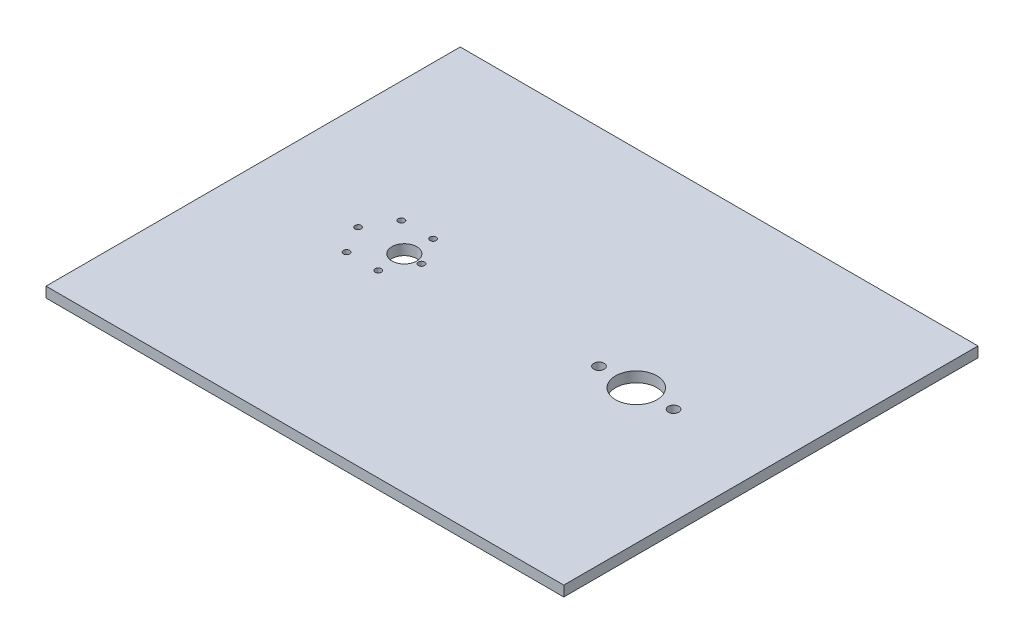
SolidWorks part; units mm, degrees
ref_plane "Front Plane" through (0, 0, 0) normal (0, 0, 1) x (1, 0, 0)
ref_plane "Top Plane" through (0, 0, 0) normal (0, 1, 0) x (1, 0, 0)
ref_plane "Right Plane" through (0, 0, 0) normal (1, 0, 0) x (0, 0, -1)
sketch "Sketch1" plane through (0, 0, 0) normal (0, 1, 0) x (1, 0, 0)
  line L0 (-125, 0) -> (125, 0) construction
  line L1 (-125, 100) -> (125, 100)
  line L2 (-125, 100) -> (-125, -100)
  line L3 (-125, -100) -> (125, -100)
  line L4 (125, 100) -> (125, -100)
  line L5 (-125, 100) -> (125, -100) construction
  line L6 (-125, -100) -> (125, 100) construction
  circle A0 centre (60, 0) radius 10
  circle A1 centre (78, 0) radius 2.5
  circle A2 centre (42, 0) radius 2.5
  circle A4 centre (-43.7, 0) radius 1.5
  circle A5 centre (-51.35, -13.2502) radius 1.5
  circle A6 centre (-66.65, -13.2502) radius 1.5
  circle A7 centre (-74.3, 0) radius 1.5
  circle A8 centre (-66.65, 13.2502) radius 1.5
  circle A9 centre (-51.35, 13.2502) radius 1.5
  circle A10 centre (-52, 0) radius 6
  point P0 (0, 0)
  point P31 (-59, 0)
  dimension "D3" = 20
  dimension "D4" = 5
  dimension "D5" = 5
  dimension "D9" = 112
  dimension "D10" = 3
  dimension "D12" = 12
  dimension "D1" = 250
  dimension "D2" = 200
  dimension "D6" = 18
  dimension "D7" = 18
  dimension "D8" = 65
  dimension "D13" = 8.3
  dimension "D14" = 22.3
  dimension "D11" = 6
extrude "Boss-Extrude1" add sketch "Sketch1" along normal blind 5
